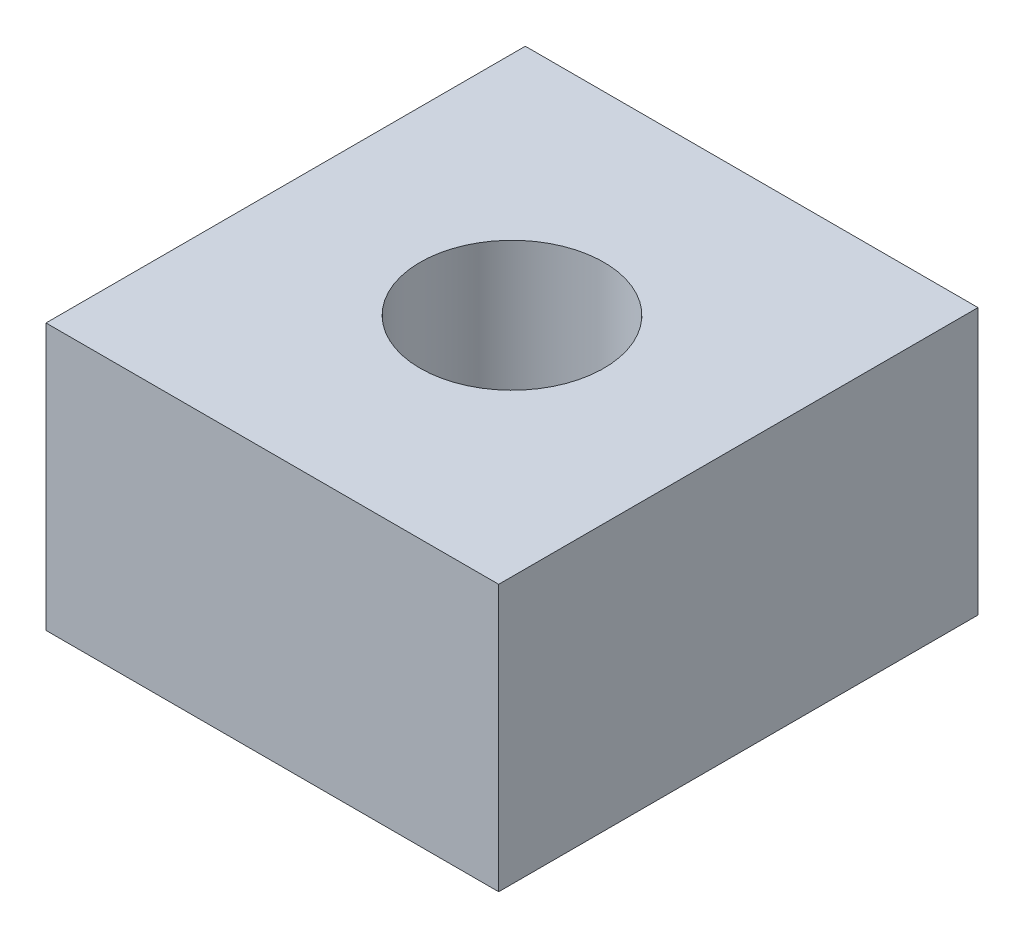
SolidWorks part; units mm, degrees
material "Polybutadiene (PB)"
ref_plane "Front Plane" through (0, 0, 0) normal (0, 0, 1) x (1, 0, 0)
ref_plane "Top Plane" through (0, 0, 0) normal (0, 1, 0) x (1, 0, 0)
ref_plane "Right Plane" through (0, 0, 0) normal (1, 0, 0) x (0, 0, -1)
sketch "Sketch1" plane through (0, 0, 0) normal (0, 1, 0) x (1, 0, 0)
  line L1 (0, 0) -> (17, 0)
  line L2 (0, 0) -> (0, 18)
  line L3 (0, 18) -> (17, 18)
  line L4 (17, 0) -> (17, 18)
  dimension "D1" = 18
  dimension "D2" = 17
extrude "Boss-Extrude1" add sketch "Sketch1" along normal blind 10
sketch "Sketch2" plane through (0, 10, 0) normal (0, 1, 0) x (1, 0, 0)
  line L0 (0, 18) -> (17, 0) construction
  circle A0 centre (8.5, 9) radius 3.45
  dimension "D1" = 6.9
extrude "Cut-Extrude1" cut sketch "Sketch2" against normal blind 10
